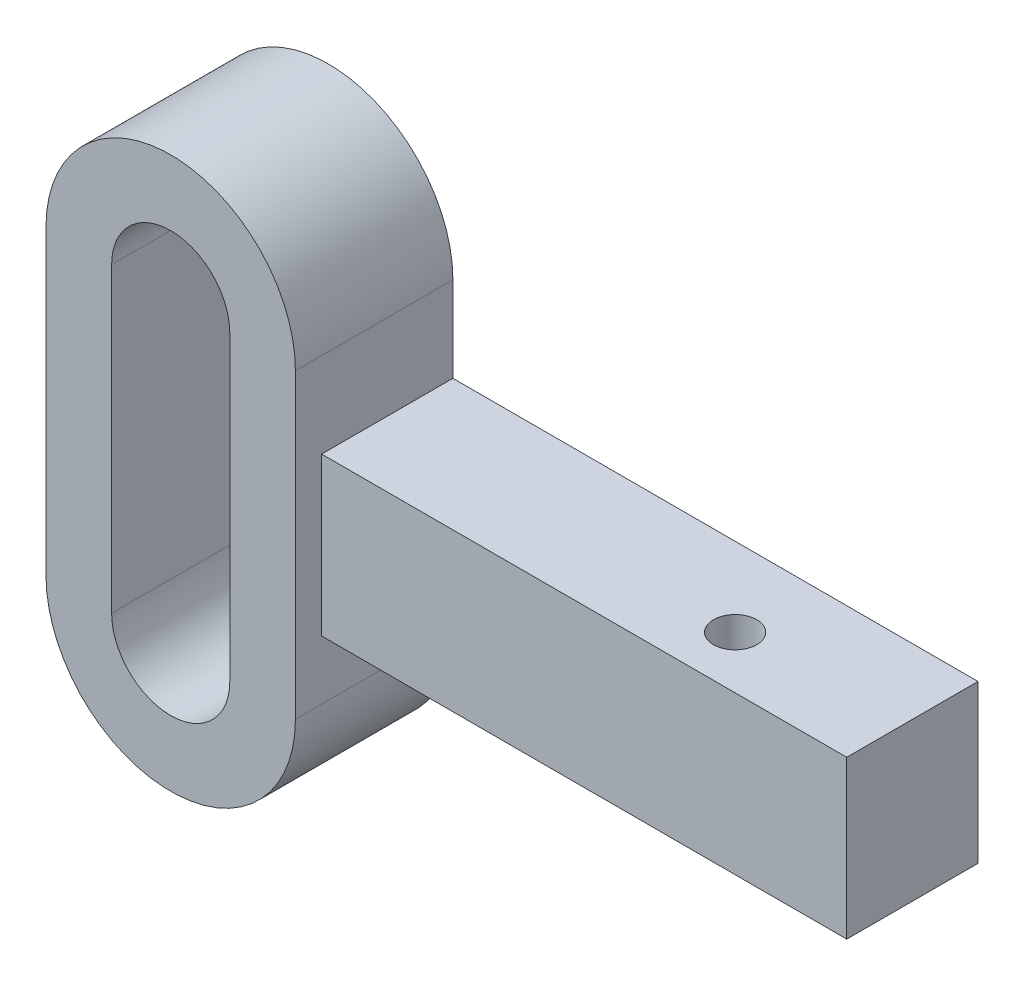
SolidWorks part; units mm, degrees
ref_plane "Front Plane" through (0, 0, 0) normal (0, 0, 1) x (1, 0, 0)
ref_plane "Top Plane" through (0, 0, 0) normal (0, 1, 0) x (1, 0, 0)
ref_plane "Right Plane" through (0, 0, 0) normal (1, 0, 0) x (0, 0, -1)
sketch "Sketch1" plane through (0, 0, 0) normal (0, 0, 1) x (1, 0, 0)
  line L0 (0, 11.5) -> (0, -11.5) construction
  line L1 (0, -55) -> (0, 55) construction
  line L2 (4.5, 11.5) -> (4.5, -11.5)
  line L3 (-4.5, 11.5) -> (-4.5, -11.5)
  line L4 (55, 0) -> (-55, 0) construction
  arc A0 (4.5, 11.5) -> (-4.5, 11.5) centre (0, 11.5) ccw
  arc A1 (-4.5, -11.5) -> (4.5, -11.5) centre (0, -11.5) ccw
  point P5 (0, 0)
  point P10 (0, 16)
  point P11 (0, -16)
  dimension "D1" = 32
  dimension "D2" = 0
  dimension "D3" = 4.5
sketch "Sketch3" plane through (0, 0, 0) normal (0, 0, 1) x (1, 0, 0)
  line L0 (0, 11.5) -> (0, -11.5) construction
  line L1 (0, -55) -> (0, 55) construction
  line L2 (9.5, 11.5) -> (9.5, -11.5)
  line L3 (-9.5, 11.5) -> (-9.5, -11.5)
  line L4 (55, 0) -> (-55, 0) construction
  arc A0 (9.5, 11.5) -> (-9.5, 11.5) centre (0, 11.5) ccw
  arc A1 (-9.5, -11.5) -> (9.5, -11.5) centre (0, -11.5) ccw
  point P5 (0, 0)
  point P10 (0, 21)
  point P11 (0, -21)
  dimension "D1" = 42
  dimension "D2" = 21
  dimension "D3" = 9.5
extrude "Boss-Extrude1" add sketch "Sketch3" along normal blind 12
extrude "Cut-Extrude1" cut sketch "Sketch1" along normal through all
sketch "Sketch4" plane through (0, 0, 0) normal (0, 0, 1) x (1, 0, 0)
  line L0 (9.5, -11.5) -> (9.5, 11.5) construction
  line L1 (9.5, 5) -> (49.5, 5)
  line L2 (9.5, 5) -> (9.5, -7)
  line L3 (9.5, -7) -> (49.5, -7)
  line L4 (49.5, 5) -> (49.5, -7)
  line L5 (55, 0) -> (-55, 0) construction
  dimension "D1" = 40
  dimension "D2" = 5
  dimension "D3" = 12
extrude "Boss-Extrude2" add sketch "Sketch4" along normal blind 10
hole_wizard "M4 Tapped Hole1" positions "Sketch5" profile "Sketch6" tap size "M4" standard "DIN" end condition through all
sketch "Sketch5" plane through (0, -7, 0) normal (0, -1, 0) x (-1, 0, 0)
  line L0 (-9.5, 0) -> (-49.5, 0) construction
  line L1 (-9.5, -12) -> (-9.5, 0) construction
  point P0 (-37, -6)
  dimension "D1" = 6
  dimension "D2" = 27.5
sketch "Sketch6" plane through (37, -7, 6) normal (1, 0, 0) x (0, 0, -1)
  line L0 (0, 0) -> (0, 28)
  line L1 (0, 28) -> (1.65, 28)
  line L2 (1.65, 28) -> (1.65, 0)
  line L5 (1.65, 0) -> (0, 0)
  line L11 (0, -6.35) -> (0, 107.95) construction
  dimension "Thru Tap Drill Dia." = 3.3
  dimension "Thru Tap Drill Depth" = 28
cosmetic thread "Hole Thread1" parameters "D2"=4
